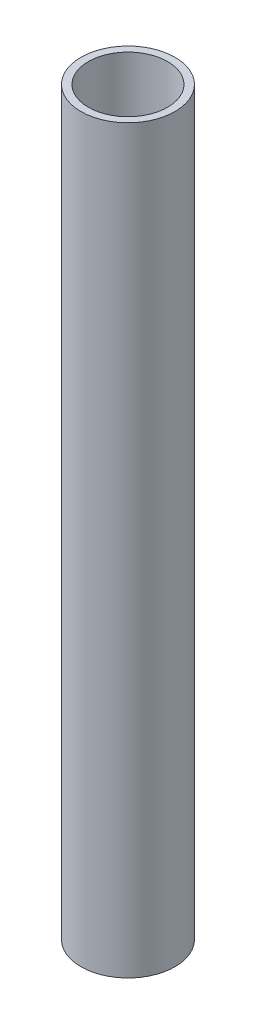
SolidWorks part; units mm, degrees
ref_plane "Front Plane" through (0, 0, 0) normal (0, 0, 1) x (1, 0, 0)
ref_plane "Top Plane" through (0, 0, 0) normal (0, 1, 0) x (1, 0, 0)
ref_plane "Right Plane" through (0, 0, 0) normal (1, 0, 0) x (0, 0, -1)
sketch "Sketch1" plane through (0, 0, 0) normal (0, 1, 0) x (1, 0, 0)
  circle A0 centre (0, 0) radius 12.7
  circle A1 centre (0, 0) radius 10.7
  dimension "D1" = 2
  dimension "D2" = 25.4
extrude "Boss-Extrude1" add sketch "Sketch1" along normal blind 200
